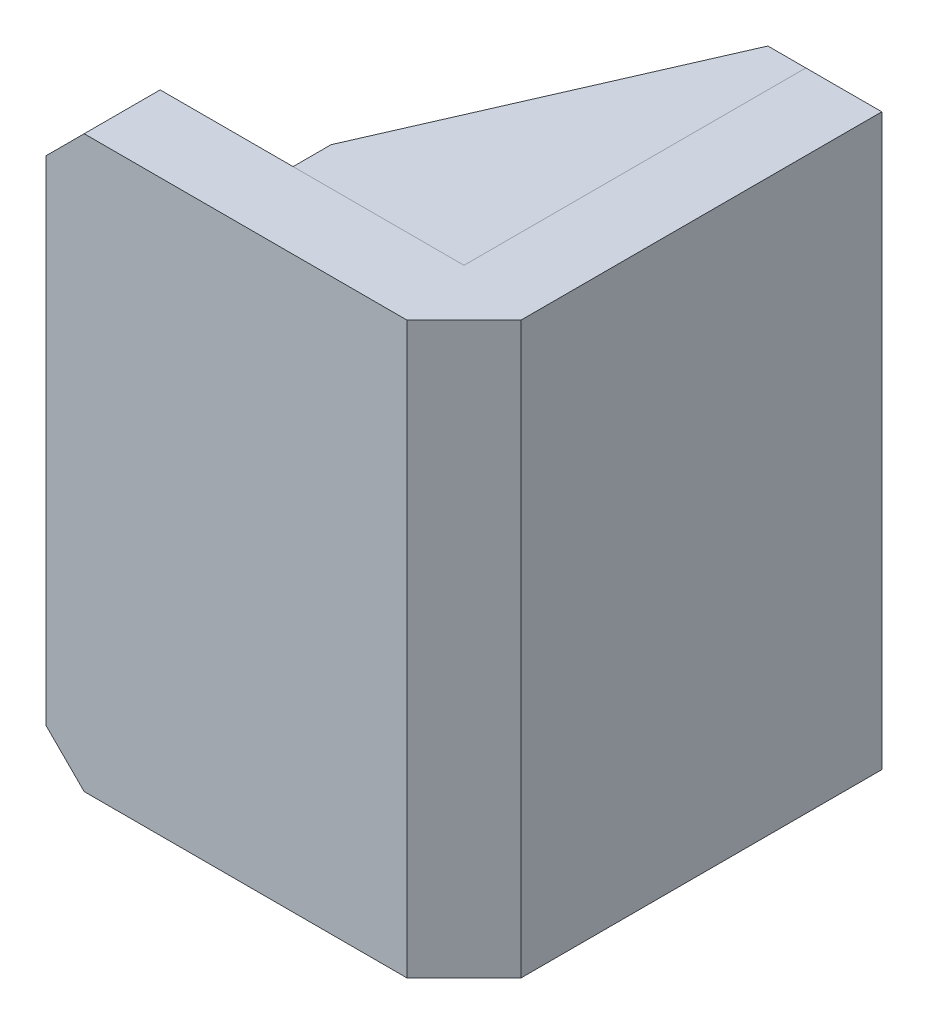
SolidWorks part; units mm, degrees
ref_plane "前视基准面" through (0, 0, 0) normal (0, 0, 1) x (1, 0, 0)
ref_plane "上视基准面" through (0, 0, 0) normal (0, 1, 0) x (1, 0, 0)
ref_plane "右视基准面" through (0, 0, 0) normal (1, 0, 0) x (0, 0, -1)
sketch "草图1" plane through (0, 0, 0) normal (0, 0, 1) x (1, 0, 0)
  line L1 (-45, 75) -> (45, 75)
  line L2 (-45, 75) -> (-45, -75)
  line L3 (-45, -75) -> (45, -75)
  line L4 (45, 75) -> (45, -75)
  line L5 (-45, 75) -> (45, -75) construction
  line L6 (-45, -75) -> (45, 75) construction
  point P0 (0, 0)
  dimension "D1" = 150
  dimension "D2" = 90
extrude "凸台-拉伸1" add sketch "草图1" along normal blind 20
sketch "草图2" plane through (45, 0, 0) normal (1, 0, 0) x (0, 0, -1)
  line L0 (-20, 75) -> (0, 75) construction
  line L1 (-20, -75) -> (90, -75)
  line L2 (-20, -75) -> (-20, 75)
  line L3 (-20, 75) -> (90, 75)
  line L4 (90, -75) -> (90, 75)
  dimension "D1" = 110
extrude "凸台-拉伸2" add sketch "草图2" along normal blind 20
chamfer "倒角1" distance 10 angle 45 2 edges at (-45, -75, 10) (-45, 75, 10)
sketch "草图3" plane through (0, 75, 0) normal (0, 1, 0) x (1, 0, 0)
  line L0 (45, 90) -> (35, 90)
  line L1 (35, 90) -> (0, 10)
  line L2 (0, 10) -> (0, 0)
  line L3 (45, 0) -> (-35, 0) construction
  line L4 (0, 0) -> (45, 0)
  line L5 (45, 0) -> (45, 90)
  dimension "D1" = 10
  dimension "D2" = 10
  dimension "D3" = 45
extrude "凸台-拉伸3" add sketch "草图3" against normal blind 15 separate body
mirror "镜向1" about plane through (0, 0, 0) normal (0, 1, 0) of bodies 110
chamfer "倒角2" distance 15 angle 45 1 edges at (65, 0, 20)
equation "\"零件重量\"= \"SW-质量\""
